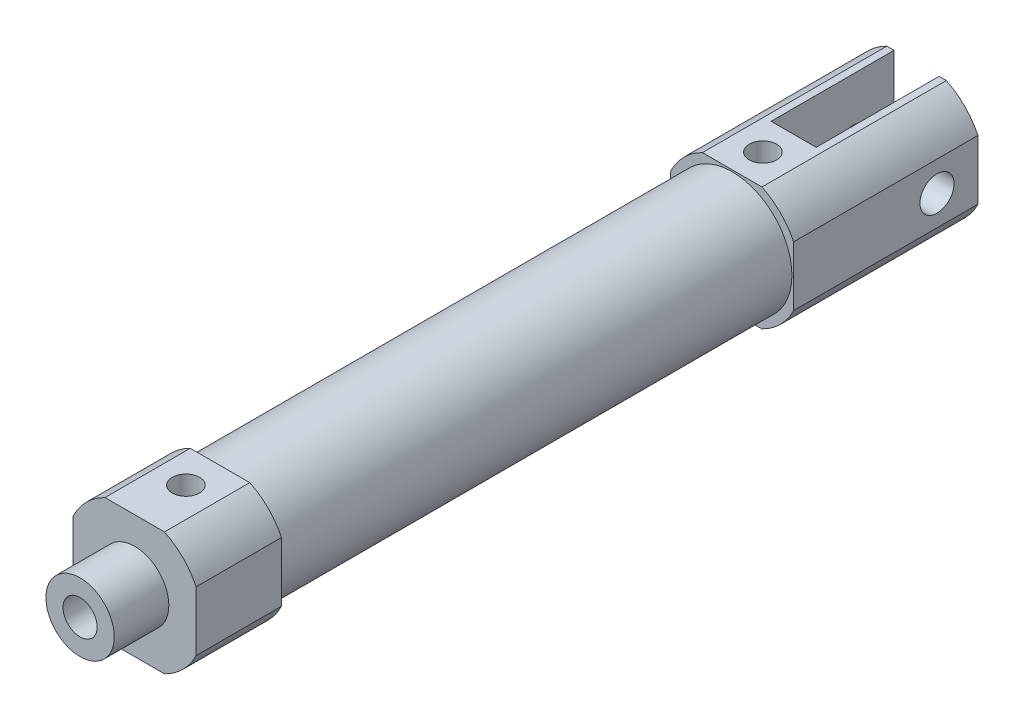
SolidWorks part; units mm, degrees
ref_plane "Front Plane" through (0, 0, 0) normal (0, 0, 1) x (1, 0, 0)
ref_plane "Top Plane" through (0, 0, 0) normal (0, 1, 0) x (1, 0, 0)
ref_plane "Right Plane" through (0, 0, 0) normal (1, 0, 0) x (0, 0, -1)
sketch "Sketch1" plane through (0, 0, 0) normal (0, 0, 1) x (1, 0, 0)
  line L1 (-4.3589, -9) -> (4.3589, -9)
  line L2 (-9, -4.3589) -> (-9, 4.3589)
  line L3 (-4.3589, 9) -> (4.3589, 9)
  line L4 (9, -4.3589) -> (9, 4.3589)
  line L5 (-7.0711, -7.0711) -> (7.0711, 7.0711) construction
  line L6 (-7.0711, 7.0711) -> (7.0711, -7.0711) construction
  arc A0 (-4.3589, 9) -> (-9, 4.3589) centre (0, 0) ccw
  arc A1 (9, 4.3589) -> (4.3589, 9) centre (0, 0) ccw
  arc A2 (4.3589, -9) -> (9, -4.3589) centre (0, 0) ccw
  arc A3 (-9, -4.3589) -> (-4.3589, -9) centre (0, 0) ccw
extrude "Boss-Extrude1" add sketch "Sketch1" along normal blind 27
sketch "Sketch2" plane through (0, 0, 27) normal (0, 0, 1) x (1, 0, 0)
  circle A0 centre (0, 0) radius 8.75
extrude "Boss-Extrude2" add sketch "Sketch2" along normal blind 75
sketch "Sketch3" plane through (0, 0, 102) normal (0, 0, 1) x (1, 0, 0)
  line L1 (-4.3589, -9) -> (4.3589, -9)
  line L2 (-9, -4.3589) -> (-9, 4.3589)
  line L3 (-4.3589, 9) -> (4.3589, 9)
  line L4 (9, -4.3589) -> (9, 4.3589)
  line L5 (-7.0711, -7.0711) -> (7.0711, 7.0711) construction
  line L6 (-7.0711, 7.0711) -> (7.0711, -7.0711) construction
  arc A0 (-9, -4.3589) -> (-4.3589, -9) centre (0, 0) ccw
  arc A1 (-4.3589, 9) -> (-9, 4.3589) centre (0, 0) ccw
  arc A2 (9, 4.3589) -> (4.3589, 9) centre (0, 0) ccw
  arc A3 (4.3589, -9) -> (9, -4.3589) centre (0, 0) ccw
extrude "Boss-Extrude3" add sketch "Sketch3" along normal blind 12.5
sketch "Sketch4" plane through (0, 0, 114.5) normal (0, 0, 1) x (1, 0, 0)
  circle A0 centre (0, 0) radius 5
extrude "Boss-Extrude4" add sketch "Sketch4" along normal blind 8
sketch "Sketch5" plane through (0, 0, 122.5) normal (0, 0, 1) x (1, 0, 0)
  circle A0 centre (0, 0) radius 2.5
extrude "Cut-Extrude1" cut sketch "Sketch5" against normal blind 50
sketch "Sketch6" plane through (0, 9, 0) normal (0, 1, 0) x (1, 0, 0)
  line L0 (8.75, -102) -> (-8.75, -102) construction
  circle A0 centre (0, -107) radius 2
  dimension "D1" = 5
extrude "Cut-Extrude2" cut sketch "Sketch6" against normal blind 4
sketch "Sketch9" plane through (0, 9, 0) normal (0, 1, 0) x (1, 0, 0)
  line L0 (0, 0) -> (3.3, 0)
  line L1 (4.3589, 0) -> (-4.3589, 0) construction
  line L2 (3.3, 0) -> (3.3, -18)
  line L3 (3.3, -18) -> (-3.3, -18)
  line L4 (-3.3, -18) -> (-3.3, 0)
  line L5 (-3.3, 0) -> (3.3, 0)
  line M1 (4.3589, 0) -> (-4.3589, 0)
extrude "Cut-Extrude4" cut sketch "Sketch9" against normal through all contours L4 L3 L2 M1
sketch "Sketch10" plane through (0, 9, 0) normal (0, 1, 0) x (1, 0, 0)
  line L0 (3.3, -18) -> (-3.3, -18) construction
  line L1 (4.3589, -27) -> (-4.3589, -27) construction
  circle A0 centre (0, -22.5) radius 2
  dimension "D1" = 4.5
extrude "Cut-Extrude5" cut sketch "Sketch10" against normal blind 4
sketch "Sketch11" plane through (-9, 0, 0) normal (-1, 0, 0) x (0, 0, 1)
  line L0 (0, 4.3589) -> (0, -4.3589) construction
  circle A0 centre (6, 0) radius 2.5
  dimension "D1" = 6
extrude "Cut-Extrude6" cut sketch "Sketch11" against normal through all
